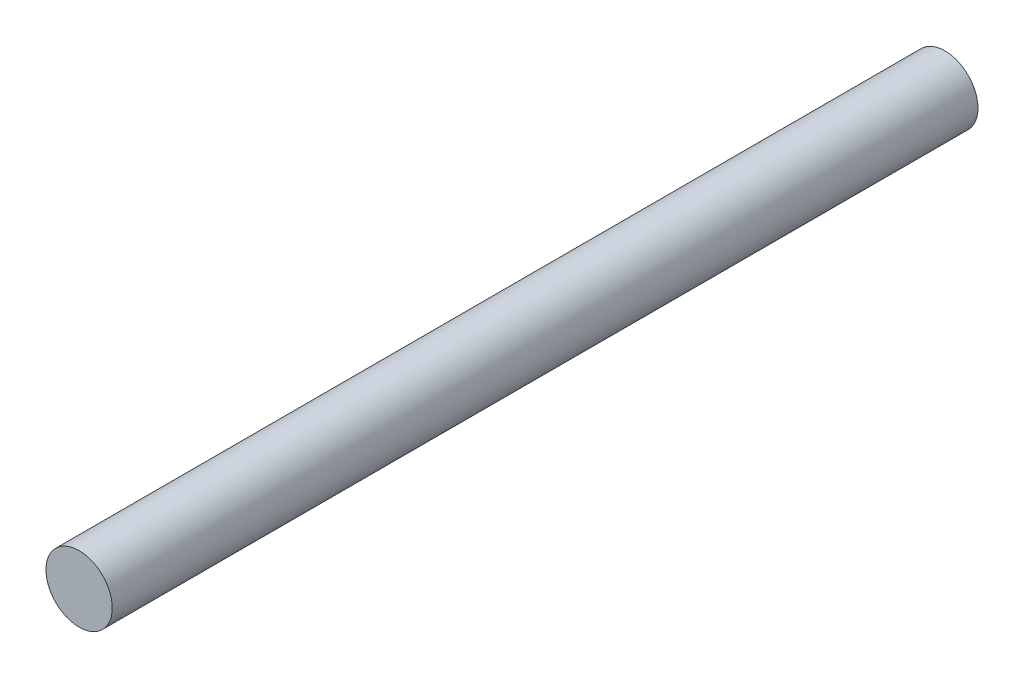
SolidWorks part; units mm, degrees
ref_plane "Front Plane" through (0, 0, 0) normal (0, 0, 1) x (1, 0, 0)
ref_plane "Top Plane" through (0, 0, 0) normal (0, 1, 0) x (1, 0, 0)
ref_plane "Right Plane" through (0, 0, 0) normal (1, 0, 0) x (0, 0, -1)
sketch "Sketch1" plane through (0, 0, 0) normal (0, 0, 1) x (1, 0, 0)
  circle A0 centre (-63.0236, 18.9325) radius 1.8
extrude "Boss-Extrude1" add sketch "Sketch1" along normal blind 47
